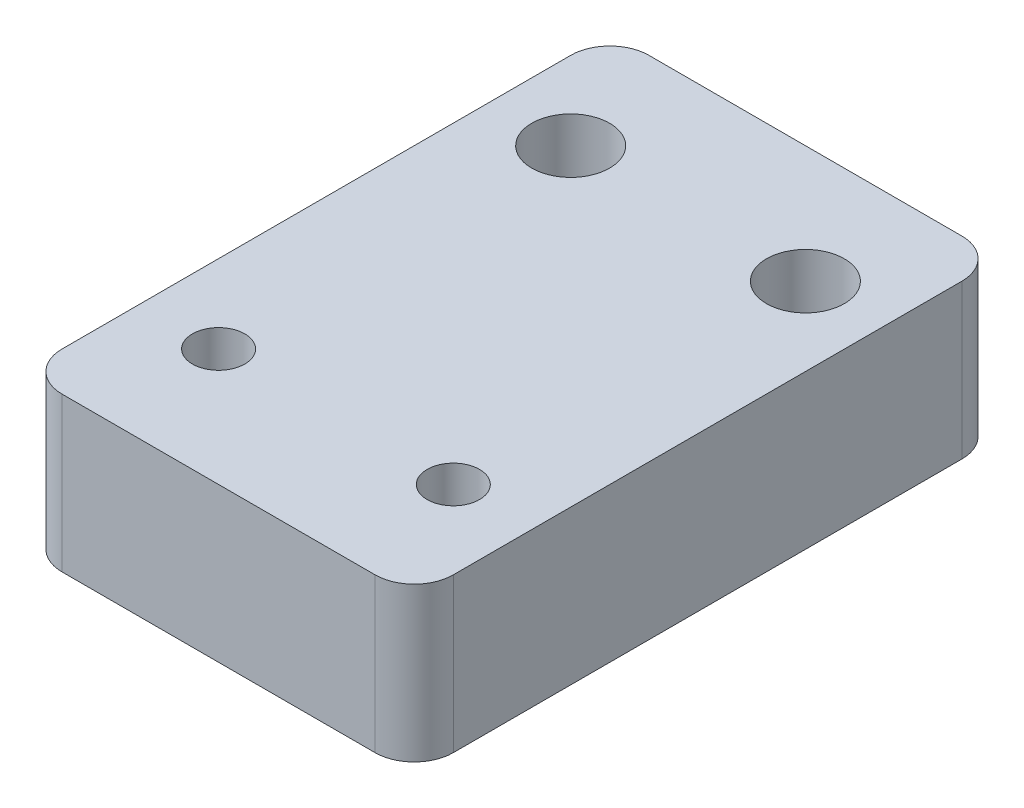
SolidWorks part; units mm, degrees
ref_plane "Front Plane" through (0, 0, 0) normal (0, 0, 1) x (1, 0, 0)
ref_plane "Top Plane" through (0, 0, 0) normal (0, 1, 0) x (1, 0, 0)
ref_plane "Right Plane" through (0, 0, 0) normal (1, 0, 0) x (0, 0, -1)
sketch "Sketch1" plane through (0, 0, 0) normal (0, 1, 0) x (1, 0, 0)
  line L0 (0, 0) -> (0, -11.43) construction
  line L5 (-12.7, -19.05) -> (12.7, -19.05)
  line L6 (-12.7, -19.05) -> (-12.7, 19.05)
  line L12 (-12.7, 19.05) -> (12.7, 19.05)
  line L13 (12.7, -19.05) -> (12.7, 19.05)
  line L14 (-12.7, -19.05) -> (12.7, 19.05) construction
  line L15 (-12.7, 19.05) -> (12.7, -19.05) construction
  line L16 (-7.62, -11.43) -> (7.62, -11.43) construction
  line L17 (0, 0) -> (0, 11.43) construction
  line L18 (-7.62, 11.43) -> (7.62, 11.43) construction
  circle A2 centre (-7.62, -11.43) radius 1.7
  circle A3 centre (7.62, -11.43) radius 1.7
  circle A4 centre (-7.62, 11.43) radius 2.5273
  circle A5 centre (7.62, 11.43) radius 2.5273
  point P0 (0, 0)
  point P10 (0, -11.43)
  point P16 (0, 11.43)
  point P19 (0, -7.0969)
  dimension "D3" = 7.62
  dimension "D4" = 5.0546
  dimension "D5" = 25.4
  dimension "D8" = 3.4
  dimension "D1" = 38.1
  dimension "D2" = 15.24
  dimension "D6" = 7.62
  dimension "D7" = 15.24
extrude "Boss-Extrude1" add sketch "Sketch1" along normal blind 10
fillet "Fillet1" radius 2.54 4 edges at (12.7, 5, 19.05) (-12.7, 5, -19.05) (12.7, 5, -19.05) (-12.7, 5, 19.05)
